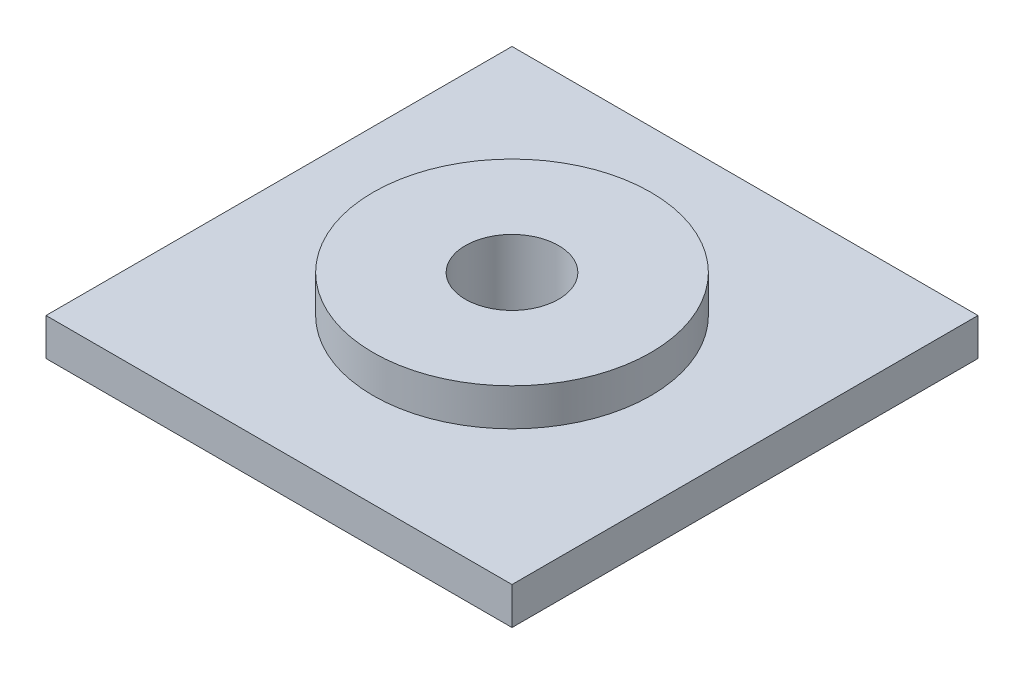
SolidWorks part; units mm, degrees
ref_plane "Front Plane" through (0, 0, 0) normal (0, 0, 1) x (1, 0, 0)
ref_plane "Top Plane" through (0, 0, 0) normal (0, 1, 0) x (1, 0, 0)
ref_plane "Right Plane" through (0, 0, 0) normal (1, 0, 0) x (0, 0, -1)
sketch "Sketch1" plane through (0, 0, 0) normal (0, 1, 0) x (1, 0, 0)
  line L1 (-12.5, -12.5) -> (12.5, -12.5)
  line L2 (-12.5, -12.5) -> (-12.5, 12.5)
  line L3 (-12.5, 12.5) -> (12.5, 12.5)
  line L4 (12.5, -12.5) -> (12.5, 12.5)
  line L5 (-12.5, -12.5) -> (12.5, 12.5) construction
  line L6 (-12.5, 12.5) -> (12.5, -12.5) construction
  point P0 (0, 0)
  dimension "D1" = 25
  dimension "D2" = 25
extrude "Boss-Extrude1" add sketch "Sketch1" along normal blind 2
sketch "Sketch2" plane through (0, 2, 0) normal (0, 1, 0) x (1, 0, 0)
  circle A0 centre (0, 0) radius 7.45
  dimension "D1" = 14.9
extrude "Boss-Extrude2" add sketch "Sketch2" along normal blind 2
sketch "Sketch3" plane through (0, 4, 0) normal (0, 1, 0) x (1, 0, 0)
  circle A0 centre (0, 0) radius 2.5
  dimension "D1" = 5
extrude "Cut-Extrude1" cut sketch "Sketch3" against normal through all
sketch "Sketch4" plane through (0, 0, 0) normal (0, 1, 0) x (1, 0, 0)
  line L0 (-12.5, 5) -> (12.5, 5) construction
  line L1 (-12.5, 12.5) -> (-12.5, -12.5) construction
  line L2 (12.5, -12.5) -> (12.5, 12.5) construction
  circle A0 centre (0, 0) radius 7.45 construction
  text T0 "<b>5 mm</b>"
  dimension "D1" = 5
extrude "Cut-Extrude2" cut sketch "Sketch4" along normal blind 1
